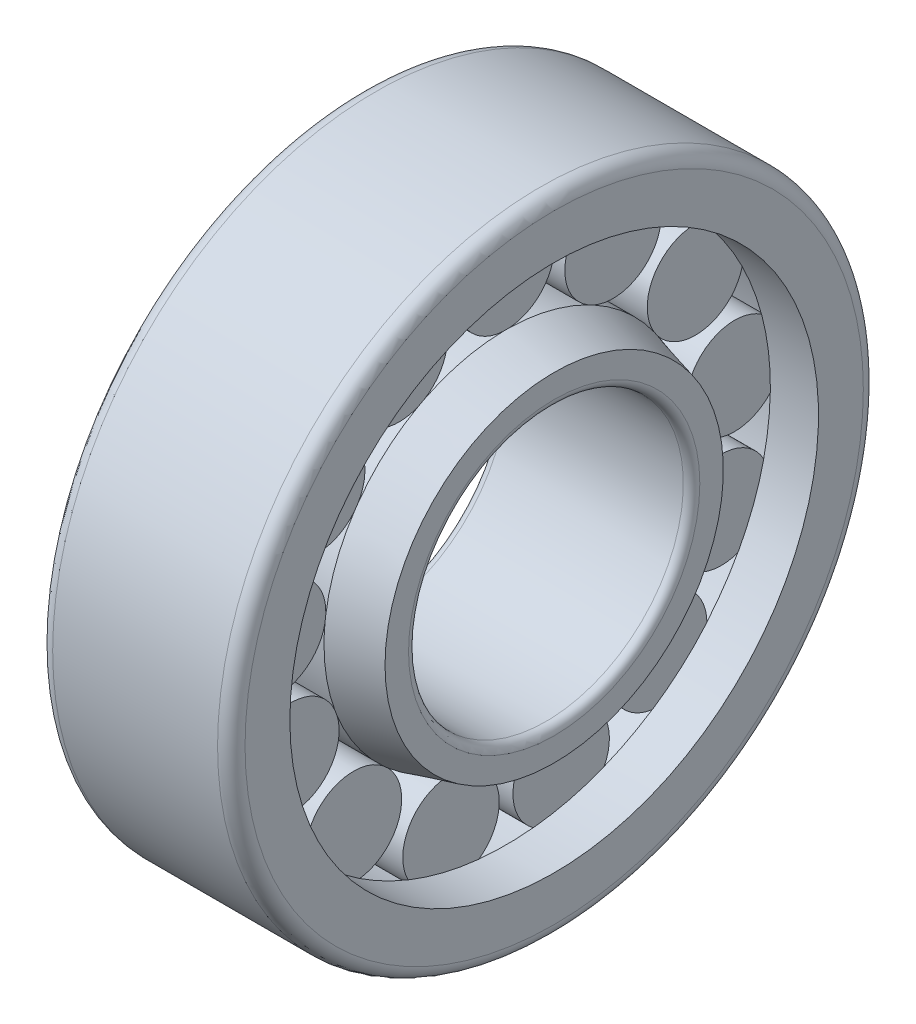
SolidWorks part; units mm, degrees
ref_plane "Front" through (0, 0, 0) normal (0, 0, 1) x (1, 0, 0)
ref_plane "Top" through (0, 0, 0) normal (0, 1, 0) x (1, 0, 0)
ref_plane "Right" through (0, 0, 0) normal (1, 0, 0) x (0, 0, -1)
sketch "Sketch1" plane through (0, 0, 0) normal (0, 0, 1) x (1, 0, 0)
  line L0 (-7, 10) -> (7, 10)
  line L1 (7, 10) -> (7, 12.3122)
  line L2 (7, 12.3122) -> (3.5, 13.25)
  line L3 (3.5, 13.25) -> (-3.5, 13.25)
  line L4 (-3.5, 13.25) -> (-7, 12.3122)
  line L5 (-7, 12.3122) -> (-7, 10)
  line L6 (-10.1379, 0) -> (10.5422, 0) construction
  dimension "B" = 14
  dimension "d" = 20
  dimension "FW" = 26.5
  dimension "D5" = 15
  dimension "D6" = 15
  dimension "D7" = 7
  dimension "D2" = 7
  dimension "D8" = 3.5
revolve "Revolve1" add sketch "Sketch1" angle 360 about L6
sketch "Sketch2" plane through (0, 0, 0) normal (0, 0, 1) x (1, 0, 0)
  line L0 (-3.5, 13.24) -> (3.5, 13.24)
  line L1 (3.5, 13.24) -> (3.5, 16.75)
  line L2 (-3.5, 16.75) -> (3.5, 16.75)
  line L3 (-3.5, 16.75) -> (-3.5, 13.24)
  line L4 (-7.1198, 0) -> (7.769, 0) construction
  line L6 (-7.4228, 16.75) -> (7.769, 16.75) construction
  dimension "D1" = 26.48
  dimension "D2" = 16.75
  dimension "D4" = 7
  dimension "D5" = 3.5
revolve "Revolve2" add sketch "Sketch2" angle 360 about L6
sketch "Sketch3" plane through (0, 0, 0) normal (0, 0, 1) x (1, 0, 0)
  line L0 (-7, 23.5) -> (7, 23.5)
  line L1 (7, 23.5) -> (7, 19.2375)
  line L2 (7, 19.2375) -> (3.49, 19.2375)
  line L3 (3.49, 19.2375) -> (3.49, 20.25)
  line L4 (3.49, 20.25) -> (-3.49, 20.25)
  line L5 (-3.49, 20.25) -> (-3.49, 19.2375)
  line L6 (-3.49, 19.2375) -> (-7, 19.2375)
  line L7 (-7, 19.2375) -> (-7, 23.5)
  line L8 (-9.0822, 0) -> (10.5352, 0) construction
  dimension "B" = 14
  dimension "DD" = 47
  dimension "D2" = 40.5
  dimension "D3" = 38.475
  dimension "D6" = 6.98
  dimension "D7" = 3.49
  dimension "D5" = 7
revolve "Revolve3" add sketch "Sketch3" angle 360 about L8
pattern_circular "Circular-Pattern1" count 13 over 360 about axis through (0, 0, 0) along (1, 0, 0) of "Revolve2"
fillet "Fillet1" radius 1 2 edges at (-7, 0, 23.5) (7, 0, 23.5)
fillet "Fillet2" radius 0.6 2 edges at (7, 0, 10) (-7, 0, 10)
equation "\"D2@Sketch1\" = \"B@Sketch1\" / 2"
equation "\"D7@Sketch1\" = \"D2@Sketch1\""
equation "\"D8@Sketch1\" = \"D7@Sketch1\"/2"
equation "\"D2@Sketch2\" = ( \"DD@Sketch3\" + \"d@Sketch1\" )  / 4"
equation "\"D4@Sketch2\" = \"B@Sketch1\" / 2"
equation "\"D5@Sketch2\" = \"D4@Sketch2\" / 2"
equation "\"D1@Sketch2\" = \"FW@Sketch1\" - 0.02"
equation "\"B@Sketch3\" = \"B@Sketch1\""
equation "\"D5@Sketch3\" = \"B@Sketch3\" / 2"
equation "\"D6@Sketch3\" = \"D5@Sketch3\" - 0.02"
equation "\"D7@Sketch3\" = \"D6@Sketch3\" / 2"
equation "\"D2@Sketch3\" = ( \"DD@Sketch3\" + \"d@Sketch1\" )  / 4 * 2 + ( ( \"DD@Sketch3\" + \"d@Sketch1\" )  / 4 * 2 - \"FW@Sketch1\"  ) "
equation "\"D3@Sketch3\" = \"D2@Sketch3\" * 0.95"
equation "\"m@Circular-Pattern1\"=int(3.14159265/atn(((\"DD@Sketch3\"+\"d@Sketch1\")/4-\"FW@Sketch1\"/2+0.02) / sqr((\"DD@Sketch3\"+\"d@Sketch1\")/4  * (\"DD@Sketch3\"+\"d@Sketch1\")/4 - ((\"DD@Sketch3\"+\"d@Sketch1\")/4-\"FW@Sketch1\"/2+0.02) *  ((\"DD@Sketch3\"+\"d@Sketch1\")/4-\"FW@Sketch1\"/2+0.02))))-1"
